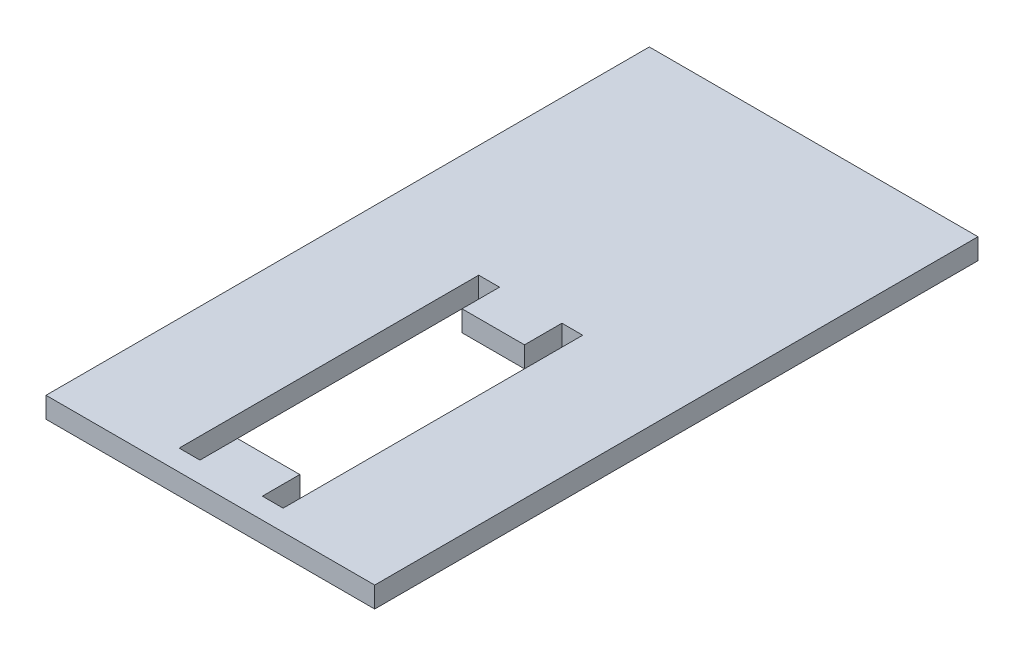
SolidWorks part; units mm, degrees
ref_plane "Plan de face" through (0, 0, 0) normal (0, 0, 1) x (1, 0, 0)
ref_plane "Plan de dessus" through (0, 0, 0) normal (0, 1, 0) x (1, 0, 0)
ref_plane "Plan de droite" through (0, 0, 0) normal (1, 0, 0) x (0, 0, -1)
sketch "Esquisse1" plane through (0, 0, 0) normal (0, 1, 0) x (1, 0, 0)
  line L1 (-43.7627, 45.3959) -> (35.2373, 45.3959)
  line L2 (-43.7627, 45.3959) -> (-43.7627, -99.6041)
  line L3 (-43.7627, -99.6041) -> (35.2373, -99.6041)
  line L4 (35.2373, 45.3959) -> (35.2373, -99.6041)
  dimension "D1" = 145
  dimension "D2" = 79
extrude "Extrusion1" add sketch "Esquisse1" along normal blind 5
sketch "Esquisse2" plane through (0, 5, 0) normal (0, 1, 0) x (1, 0, 0)
  line L0 (-43.7627, -99.6041) -> (35.2373, -99.6041) construction
  line L1 (-16.7627, -22.6041) -> (-11.7627, -22.6041)
  line L2 (-16.7627, -22.6041) -> (-16.7627, -94.6041)
  line L3 (-16.7627, -94.6041) -> (-11.7627, -94.6041)
  line L4 (-11.7627, -22.6041) -> (-11.7627, -31.6041)
  line L5 (3.2373, -22.6041) -> (8.2373, -22.6041)
  line L6 (-11.7627, -31.6041) -> (3.2373, -31.6041)
  line L7 (3.2373, -94.6041) -> (8.2373, -94.6041)
  line L8 (8.2373, -22.6041) -> (8.2373, -94.6041)
  line L9 (3.2373, -31.6041) -> (3.2373, -22.6041)
  line L10 (3.2373, -94.6041) -> (3.2373, -85.6041)
  line L11 (3.2373, -85.6041) -> (-11.7627, -85.6041)
  line L12 (-11.7627, -85.6041) -> (-11.7627, -94.6041)
  line L13 (-43.7627, 45.3959) -> (-43.7627, -99.6041) construction
  dimension "D1" = 9
  dimension "D2" = 72
  dimension "D3" = 5
  dimension "D4" = 5
  dimension "D5" = 5
  dimension "D6" = 9
  dimension "D7" = 25
  dimension "D8" = 27
extrude "Extrusion2" cut sketch "Esquisse2" against normal up to next
